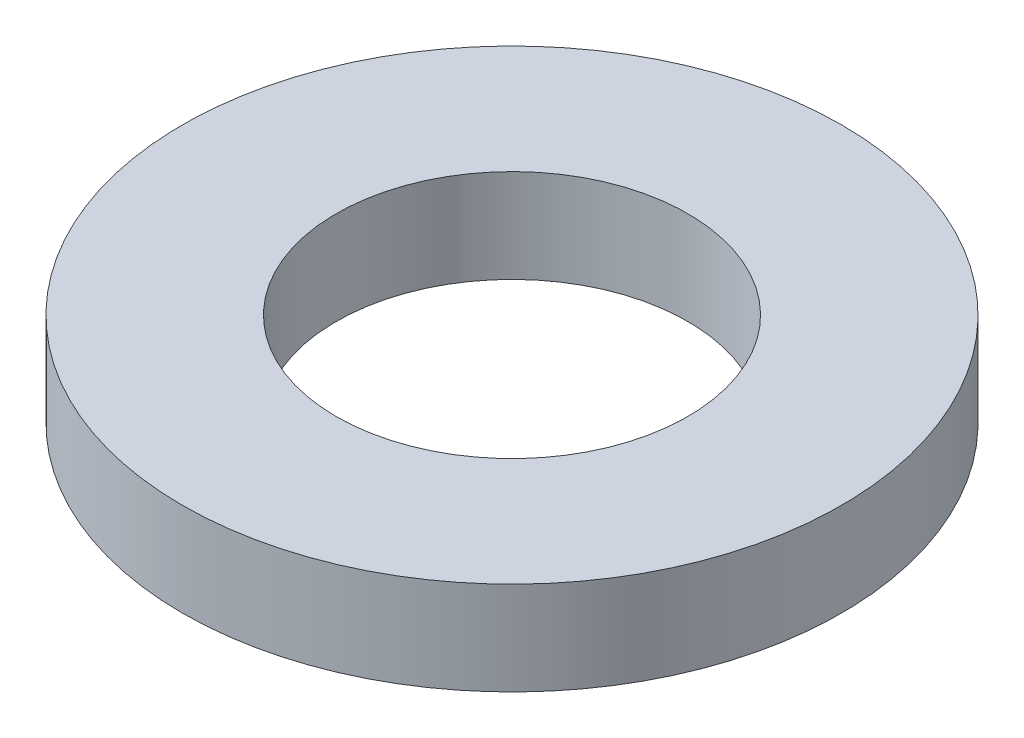
SolidWorks part; units mm, degrees
material "Nylon-6/10"
ref_plane "Front Plane" through (0, 0, 0) normal (0, 0, 1) x (1, 0, 0)
ref_plane "Top Plane" through (0, 0, 0) normal (0, 1, 0) x (1, 0, 0)
ref_plane "Right Plane" through (0, 0, 0) normal (1, 0, 0) x (0, 0, -1)
sketch "Sketch1" plane through (0, 0, 0) normal (0, 1, 0) x (1, 0, 0)
  circle A0 centre (0, 0) radius 6
  circle A1 centre (0, 0) radius 3.2
  dimension "D1" = 12
  dimension "D2" = 6.4
extrude "Boss-Extrude1" add sketch "Sketch1" along normal blind 1.7
